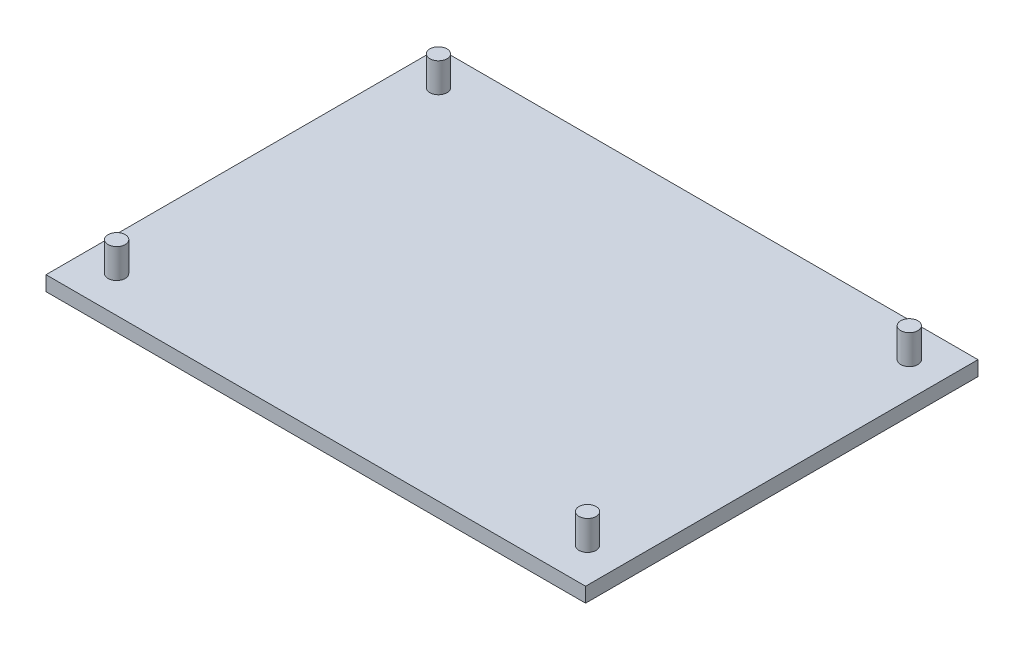
SolidWorks part; units mm, degrees
ref_plane "Plan de face" through (0, 0, 0) normal (0, 0, 1) x (1, 0, 0)
ref_plane "Plan de dessus" through (0, 0, 0) normal (0, 1, 0) x (1, 0, 0)
ref_plane "Plan de droite" through (0, 0, 0) normal (1, 0, 0) x (0, 0, -1)
sketch "Esquisse1" plane through (0, 0, 0) normal (0, 1, 0) x (1, 0, 0)
  line L1 (-55, -40) -> (55, -40)
  line L2 (-55, -40) -> (-55, 40)
  line L3 (-55, 40) -> (55, 40)
  line L4 (55, -40) -> (55, 40)
  line L5 (-55, -40) -> (55, 40) construction
  line L6 (-55, 40) -> (55, -40) construction
  point P0 (0, 0)
  dimension "D1" = 110
  dimension "D2" = 80
extrude "Boss.-Extru.1" add sketch "Esquisse1" along normal blind 3
sketch "Esquisse2" plane through (0, 3, 0) normal (0, 1, 0) x (1, 0, 0)
  line L0 (-55, 40) -> (-55, -40) construction
  line L2 (55, 40) -> (-55, 40) construction
  circle A0 centre (-48, 33) radius 1.75
  circle A1 centre (-48, -32.6) radius 1.75
  circle A2 centre (48, -32.6) radius 1.75
  circle A3 centre (48, 33) radius 1.75
  point P8 (0, 0)
  point P9 (46.5304, 35.5127)
  point P10 (0, 0)
  point P11 (46.4086, 35.5127)
  point P12 (0, 0)
  point P13 (0, 0)
  point P14 (0, 0)
  point P15 (-47.5897, 33.2585)
  point P18 (0, 0)
  dimension "D1" = 3.5
  dimension "D2" = 3.5
  dimension "D3" = 3.5
  dimension "D4" = 3.5
  dimension "D5" = 96
  dimension "D6" = 65.6
  dimension "D7" = 65.6
  dimension "D8" = 96
  dimension "D9" = 7
  dimension "D10" = 7
extrude "Boss.-Extru.2" add sketch "Esquisse2" along normal blind 6
